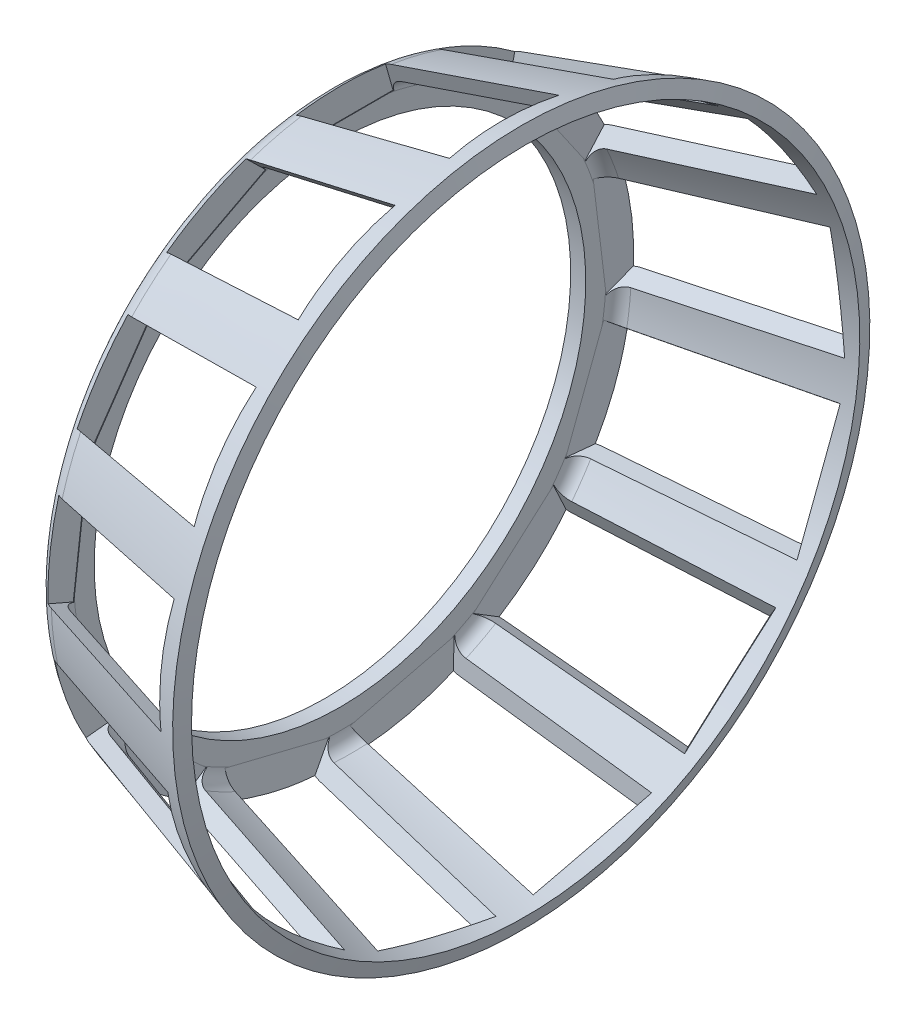
SolidWorks part; units mm, degrees
ref_plane "Plan1" through (0, 0, 0) normal (0, 0, 1) x (1, 0, 0)
ref_plane "Plan2" through (0, 0, 0) normal (0, 1, 0) x (1, 0, 0)
ref_plane "Plan3" through (0, 0, 0) normal (1, 0, 0) x (0, 0, -1)
sketch "Esquisse1" plane through (0, 0, 0) normal (0, 0, 1) x (1, 0, 0)
  line L0 (-14.7804, 19.5461) -> (-3.19, 23.0897)
  line L1 (-16.1957, 17.6335) -> (-16.1957, 16.2821)
  line L2 (-3.19, 23.0897) -> (-2.8976, 22.1334)
  line L3 (-2.8976, 22.1334) -> (-14.4881, 18.5898)
  line L4 (-15.1957, 17.6335) -> (-15.1957, 16.2821)
  line L5 (-15.1957, 16.2821) -> (-16.1957, 16.2821)
  line L6 (-3.3856, 0) -> (-14, 0) construction
  line L9 (-8.6928, 0) -> (-8.6928, 23.7971) construction
  line L10 (-30.3963, 12.0714) -> (3.0887, 22.0003) construction
  line L12 (-14, 15.1559) -> (-14, -15.1559) construction
  line L13 (-3.3856, 18) -> (-3.3856, -18) construction
  line L14 (8.3922, 23.5728) -> (-71.107, 0) construction
  line L15 (0, 0) -> (-29.1339, 0) construction
  arc A0 (-15.1957, 17.6335) -> (-14.4881, 18.5898) centre (-14.1957, 17.6335) cw
  arc A1 (-16.1957, 17.6335) -> (-14.7804, 19.5461) centre (-14.1957, 17.6335) cw
  point P13 (-16.1957, 19.1135)
  point P14 (-8.6928, 20.3616)
  point P19 (-8.6928, 0)
  dimension "D4" = 1
  dimension "D7" = 2
  dimension "D1" = 1
  dimension "D2" = 17
  dimension "D3" = 2
  dimension "D5" = 1
  dimension "D8" = 13.6
revolve "Base-Révolution" add sketch "Esquisse1" angle 360 about L6
sketch "Esquisse3" plane through (0, 0, 0) normal (0, 0, 1) x (1, 0, 0)
  line L0 (-3.19, 23.0897) -> (-10.9932, 20.704) construction
  line L1 (-3.19, 23.0897) -> (-3.19, -23.0897) construction
  line L2 (-3.19, 23.0897) -> (-14.7804, 19.5461) construction
ref_plane "Plan4" through (-8.9852, 21.3179, 0) normal (-0.2924, 0.9563, 0) x (0, 0, -1)
sketch "Esquisse4" plane through (-8.9852, 21.3179, 0) normal (-0.2924, 0.9563, 0) x (0, 0, -1)
  line L0 (0, 9.5066) -> (0, -9.0797) construction
  line L1 (0, 0.8779) -> (0, 11.0284) construction
  line L3 (2.8781, 6.4289) -> (3.5126, -4.6902)
  line L4 (-2.8781, 6.4289) -> (-3.5126, -4.6902)
  line L5 (-2.8781, 6.4289) -> (2.8781, 6.4289)
  line L6 (3.5126, -4.6902) -> (-3.5126, -4.6902)
  line L7 (3.3792, 6.4246) -> (4.2634, -9.0695) construction
  line L8 (-4.5399, -4.1902) -> (5.2637, -4.1902) construction
  line L9 (-4.0136, 5.9289) -> (3.0924, 5.9289) construction
  line L11 (3.9849, -4.1902) -> (3.4075, 5.9289) construction
  point P9 (0, -4.6902)
  point P12 (0, 6.4289)
  dimension "D1" = 0.5
  dimension "D2" = 0.5
  dimension "D3" = 0.5
extrude "Enlèv. mat.-Extru.1" cut sketch "Esquisse4" against normal blind 2 draft 20
pattern_circular "Répétition circulaire1" count 13 over 360 about axis through (-3.3856, 0, 0) along (-1, 0, 0)
